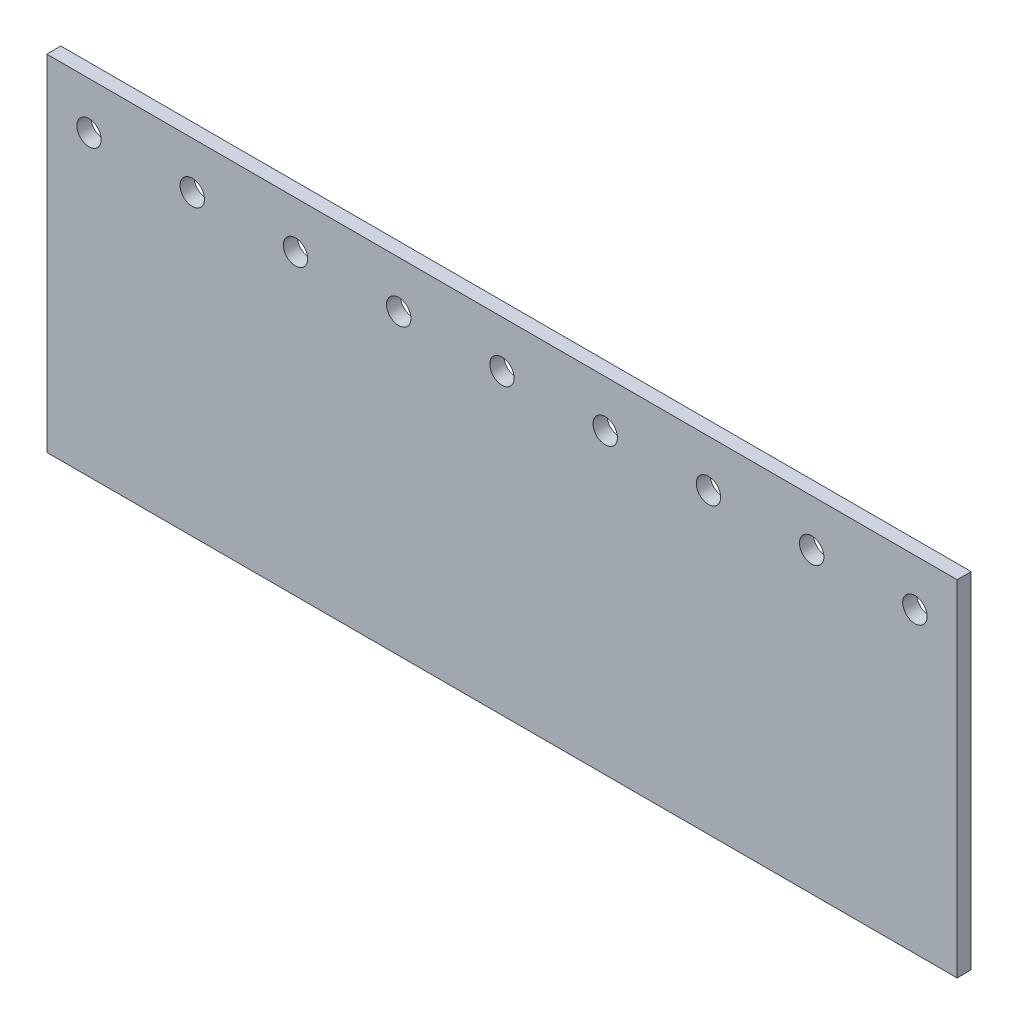
SolidWorks part; units mm, degrees
ref_plane "前视基准面" through (0, 0, 0) normal (0, 0, 1) x (1, 0, 0)
ref_plane "上视基准面" through (0, 0, 0) normal (0, 1, 0) x (1, 0, 0)
ref_plane "右视基准面" through (0, 0, 0) normal (1, 0, 0) x (0, 0, -1)
sketch "草图1" plane through (0, 0, 0) normal (0, 0, 1) x (1, 0, 0)
  line L0 (-100, 26.75) -> (100, 26.75) construction
  line L1 (-100, 36.75) -> (100, 36.75)
  line L2 (-100, 36.75) -> (-100, -36.75)
  line L3 (-100, -36.75) -> (100, -36.75)
  line L4 (100, 36.75) -> (100, -36.75)
  line L5 (-100, 36.75) -> (100, -36.75) construction
  line L6 (-100, -36.75) -> (100, 36.75) construction
  point P0 (0, 0)
  dimension "D1" = 73.5
  dimension "D2" = 200
  dimension "D3" = 10
extrude "凸台-拉伸1" add sketch "草图1" along normal blind 3
sketch "草图2" plane through (0, 0, 3) normal (0, 0, 1) x (1, 0, 0)
  line L0 (-100, 26.75) -> (100, 26.75) construction
  line L1 (-100, 36.75) -> (-100, -36.75) construction
  line L2 (100, -36.75) -> (100, 36.75) construction
  line L4 (100, 36.75) -> (-100, 36.75) construction
  circle A0 centre (0, 26.75) radius 2.6
  dimension "D1" = 5.2
  dimension "D2" = 10
extrude "切除-拉伸2" cut sketch "草图2" against normal through all both and the other way through all
pattern_linear "阵列(线性)1" count 5 spacing 22 along (1, 0, 0) count 5 spacing 22 along (-1, 0, 0) of "切除-拉伸2"
sketch "草图3" plane through (0, 0, 3) normal (0, 0, 1) x (1, 0, 0)
  line L0 (-100, -36.75) -> (100, -36.75) construction
  line L1 (-100, 36.75) -> (-97, 36.75)
  line L2 (-100, 36.75) -> (-100, -36.75)
  line L3 (-100, -36.75) -> (-97, -36.75)
  line L4 (-97, 36.75) -> (-97, -36.75)
  line L6 (100, 36.75) -> (97, 36.75)
  line L7 (100, 36.75) -> (100, -36.75)
  line L8 (100, -36.75) -> (97, -36.75)
  line L9 (97, 36.75) -> (97, -36.75)
  dimension "D1" = 3
  dimension "D2" = 3
extrude "切除-拉伸3" cut sketch "草图3" against normal through all both and the other way through all
